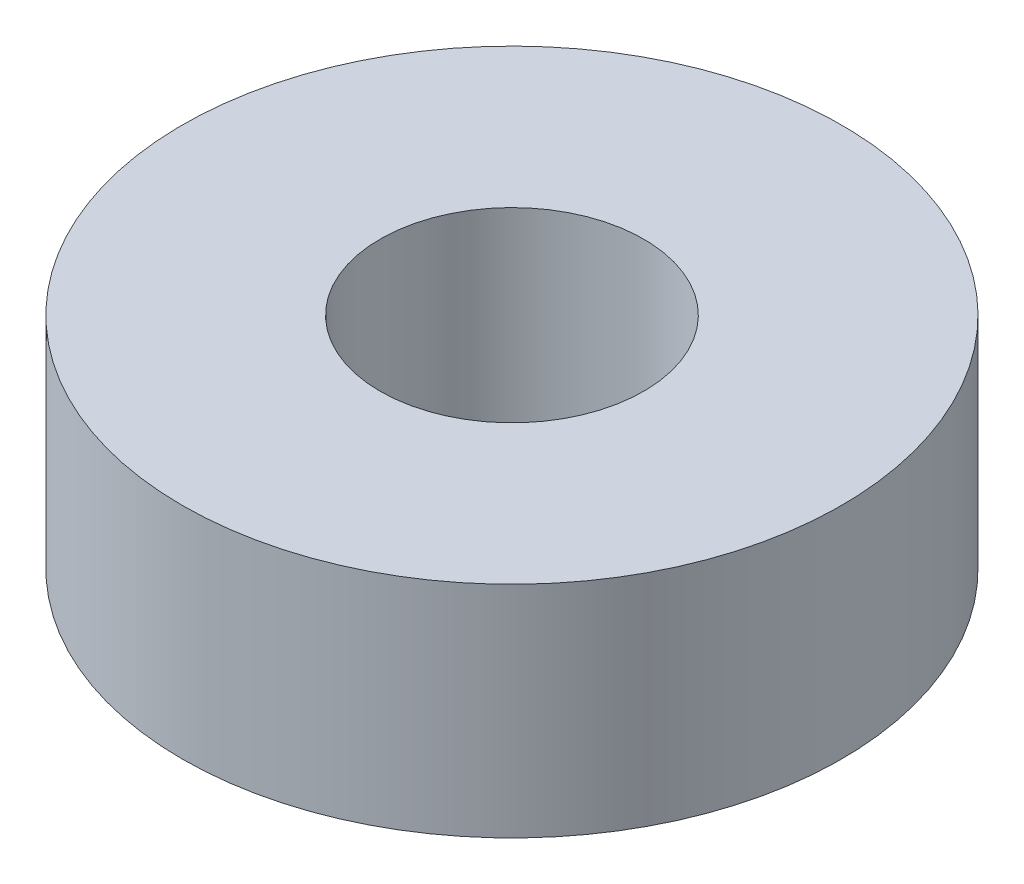
SolidWorks part; units mm, degrees
ref_plane "Front Plane" through (0, 0, 0) normal (0, 0, 1) x (1, 0, 0)
ref_plane "Top Plane" through (0, 0, 0) normal (0, 1, 0) x (1, 0, 0)
ref_plane "Right Plane" through (0, 0, 0) normal (1, 0, 0) x (0, 0, -1)
sketch "Sketch1" plane through (0, 0, 0) normal (0, 1, 0) x (1, 0, 0)
  circle A0 centre (0, 0) radius 3
  circle A1 centre (0, 0) radius 7.5
  dimension "D1" = 6
  dimension "D2" = 15
extrude "Boss-Extrude1" add sketch "Sketch1" along normal blind 5
